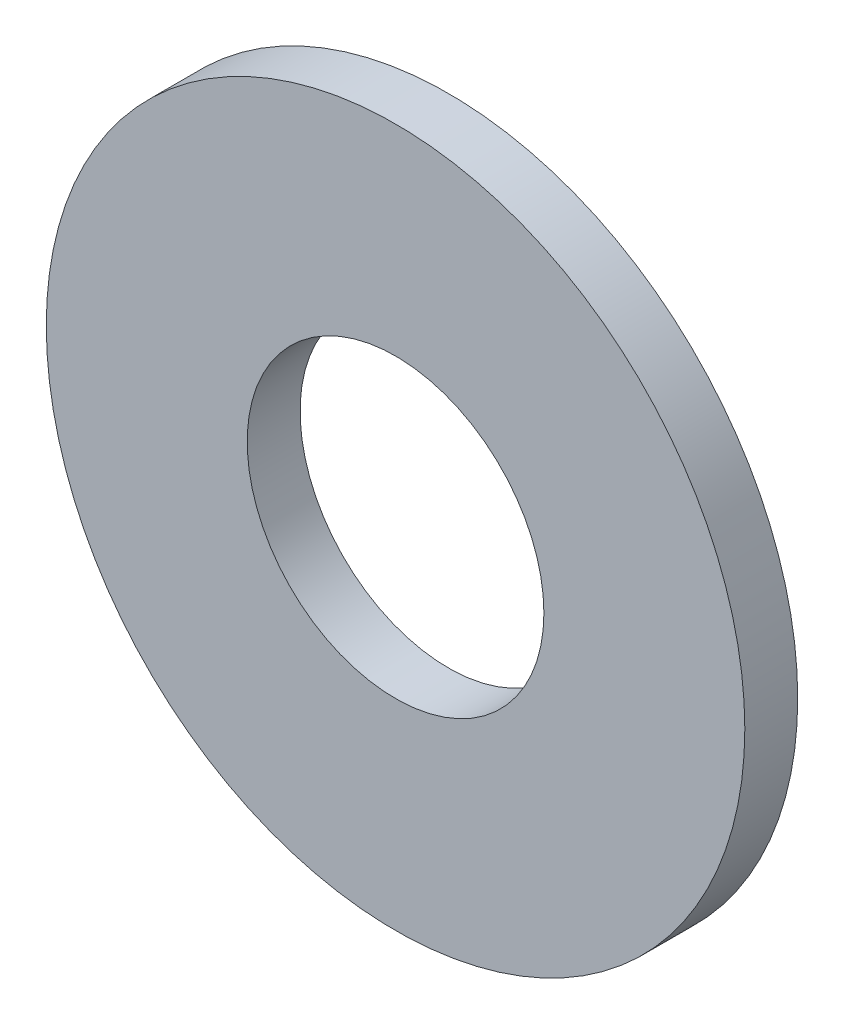
SolidWorks part; units mm, degrees
material "AISI 1045 Steel, cold drawn"
ref_plane "Front Plane" through (0, 0, 0) normal (0, 0, 1) x (1, 0, 0)
ref_plane "Top Plane" through (0, 0, 0) normal (0, 1, 0) x (1, 0, 0)
ref_plane "Right Plane" through (0, 0, 0) normal (1, 0, 0) x (0, 0, -1)
sketch "Sketch1" plane through (0, 0, 0) normal (0, 0, 1) x (1, 0, 0)
  circle A0 centre (0, 0) radius 13.081
  dimension "D1" = 26.162
extrude "BASE" add sketch "Sketch1" along normal blind 1.9812
hole_wizard "7/16 (0.4375) Diameter Hole1" positions "Sketch3" profile "Sketch2" hole size "7/16" standard "ANSI Inch" end condition through all
sketch "Sketch3" plane through (0, 0, 1.9812) normal (0, 0, 1) x (1, 0, 0)
  point P0 (0, 0)
sketch "Sketch2" plane through (0, 0, 1.9812) normal (1, 0, 0) x (0, -1, 0)
  line L0 (0, 0) -> (0, 1.9812)
  line L1 (0, 1.9812) -> (5.5562, 1.9812)
  line L2 (5.5562, 1.9812) -> (5.5562, 0)
  line L5 (5.5562, 0) -> (0, 0)
  line L11 (0, -6.35) -> (0, 107.95) construction
  dimension "Thru Hole Dia." = 11.1125
  dimension "Thru Hole Depth" = 1.9812
